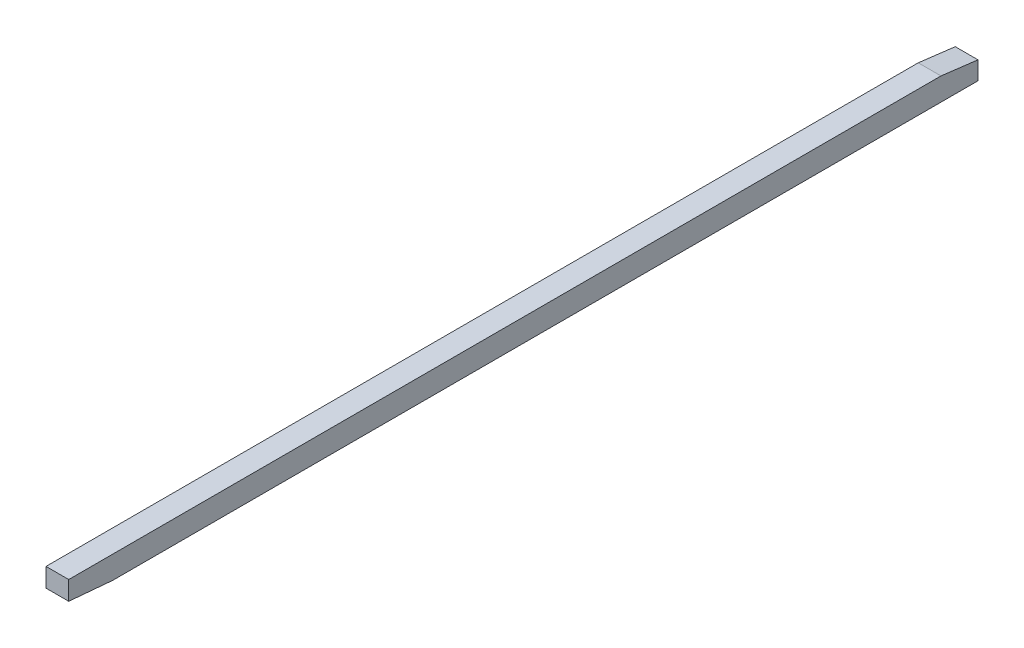
SolidWorks part; units mm, degrees
ref_plane "Front Plane" through (0, 0, 0) normal (0, 0, 1) x (1, 0, 0)
ref_plane "Top Plane" through (0, 0, 0) normal (0, 1, 0) x (1, 0, 0)
ref_plane "Right Plane" through (0, 0, 0) normal (1, 0, 0) x (0, 0, -1)
sketch "Sketch1" plane through (0, 0, 0) normal (0, 0, 1) x (1, 0, 0)
  line L1 (0, 0) -> (-2.54, 0)
  line L2 (0, 0) -> (0, 2.54)
  line L3 (0, 2.54) -> (-2.54, 2.54)
  line L4 (-2.54, 0) -> (-2.54, 2.54)
  dimension "D1" = 2.54
  dimension "D2" = 2.54
extrude "Boss-Extrude1" add sketch "Sketch1" along normal blind 101.6
chamfer "Chamfer1" distance 4.92 angle 5 1 edges at (-1.27, 0, 101.6)
chamfer "Chamfer2" distance 0.508 angle 83 1 edges at (-1.27, 2.54, 0)
